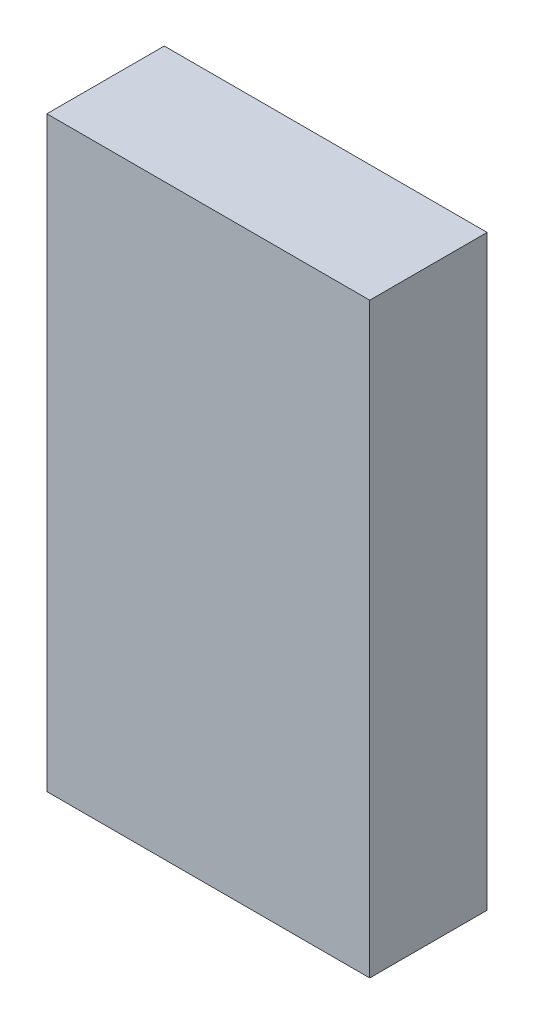
SolidWorks part; units mm, degrees
ref_plane "Front Plane" through (0, 0, 0) normal (0, 0, 1) x (1, 0, 0)
ref_plane "Top Plane" through (0, 0, 0) normal (0, 1, 0) x (1, 0, 0)
ref_plane "Right Plane" through (0, 0, 0) normal (1, 0, 0) x (0, 0, -1)
sketch "Sketch1" plane through (0, 0, 0) normal (0, 0, 1) x (1, 0, 0)
  line L1 (27.5, 50) -> (-27.5, 50)
  line L2 (27.5, 50) -> (27.5, -50)
  line L3 (27.5, -50) -> (-27.5, -50)
  line L4 (-27.5, 50) -> (-27.5, -50)
  line L5 (0, -50) -> (0, 50) construction
  line L6 (27.5, 0) -> (-27.5, 0) construction
  point P0 (0, 0)
  dimension "D1" = 55
  dimension "D2" = 100
extrude "Boss-Extrude1" add sketch "Sketch1" along normal blind 20
